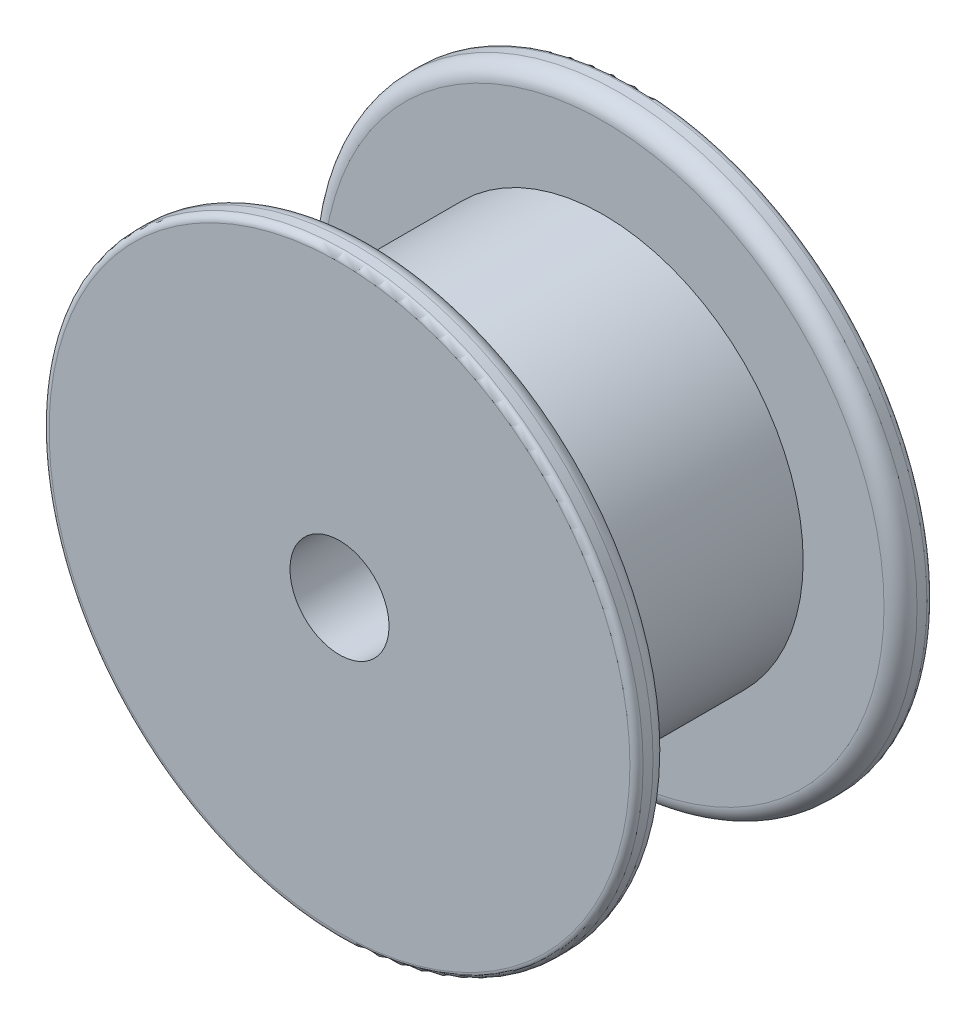
SolidWorks part; units mm, degrees
ref_plane "Front Plane" through (0, 0, 0) normal (0, 0, 1) x (1, 0, 0)
ref_plane "Top Plane" through (0, 0, 0) normal (0, 1, 0) x (1, 0, 0)
ref_plane "Right Plane" through (0, 0, 0) normal (1, 0, 0) x (0, 0, -1)
sketch "Sketch1" plane through (0, 0, 0) normal (0, 0, 1) x (1, 0, 0)
  circle A0 centre (69.6856, 5.6914) radius 6.05
  dimension "D1" = 12.1
extrude "Boss-Extrude1" add sketch "Sketch1" along normal blind 7
sketch "Sketch4" plane through (0, 0, 7) normal (0, 0, 1) x (1, 0, 0)
  circle A0 centre (69.6856, 5.6914) radius 9
extrude "Boss-Extrude2" add sketch "Sketch4" along normal blind 1
sketch "Sketch6" plane through (0, 0, 0) normal (0, 0, -1) x (-1, 0, 0)
  circle A0 centre (-69.6856, 5.6914) radius 9
extrude "Boss-Extrude3" add sketch "Sketch6" along normal blind 1
fillet "Fillet1" radius 0.5 1 edges at (60.6856, 5.6914, 0)
fillet "Fillet2" radius 0.5 1 edges at (78.6856, 5.6914, 7)
fillet "Fillet3" radius 0.2 1 edges at (78.6856, 5.6914, 8)
fillet "Fillet4" radius 0.2 1 edges at (60.6856, 5.6914, -1)
sketch "Sketch11" plane through (0, 0, -1) normal (0, 0, -1) x (-1, 0, 0)
  circle A0 centre (-69.6856, 5.6914) radius 1.5
  circle A1 centre (-69.6856, 5.6914) radius 8.8 construction
  dimension "D1" = 0
extrude "Cut-Extrude1" cut sketch "Sketch11" against normal through all
